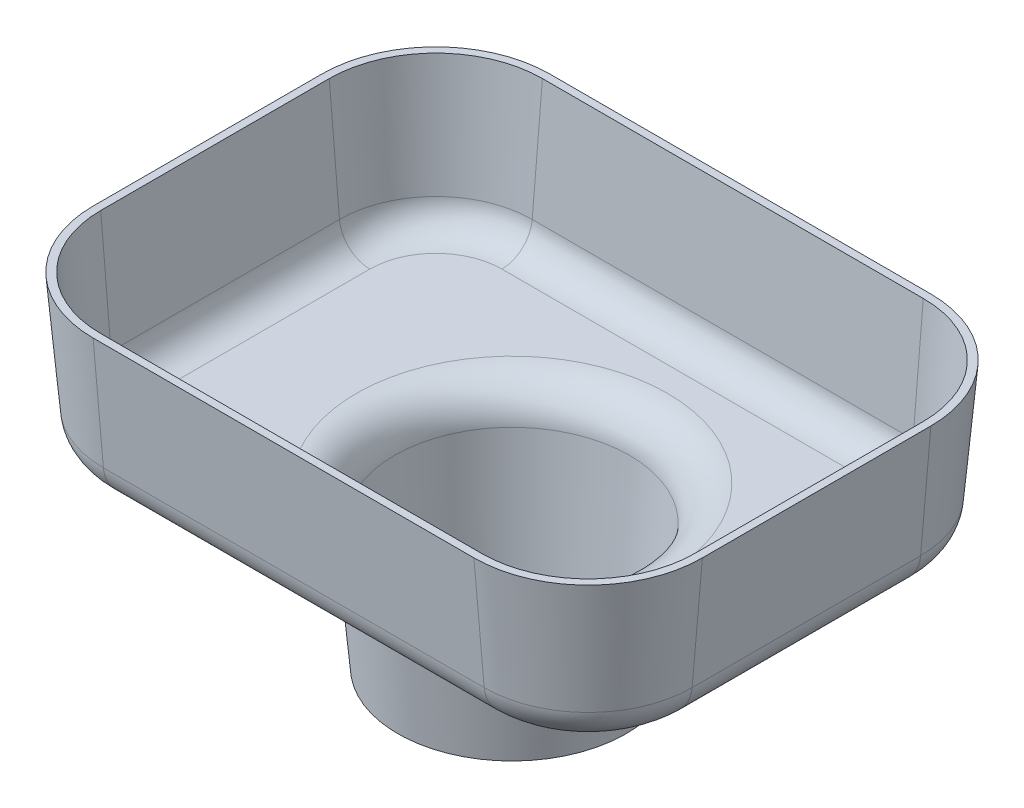
SolidWorks part; units mm, degrees
ref_plane "Front Plane" through (0, 0, 0) normal (0, 0, 1) x (1, 0, 0)
ref_plane "Top Plane" through (0, 0, 0) normal (0, 1, 0) x (1, 0, 0)
ref_plane "Right Plane" through (0, 0, 0) normal (1, 0, 0) x (0, 0, -1)
sketch "Sketch1" plane through (0, 0, 0) normal (0, 1, 0) x (1, 0, 0)
  line L1 (31.75, -38.1) -> (-31.75, -38.1)
  line L2 (50.8, -19.05) -> (50.8, 19.05)
  line L3 (31.75, 38.1) -> (-31.75, 38.1)
  line L4 (-50.8, -19.05) -> (-50.8, 19.05)
  line L5 (50.8, -38.1) -> (-50.8, 38.1) construction
  line L6 (50.8, 38.1) -> (-50.8, -38.1) construction
  arc A0 (-50.8, 19.05) -> (-31.75, 38.1) centre (-31.75, 19.05) cw
  arc A1 (-50.8, -19.05) -> (-31.75, -38.1) centre (-31.75, -19.05) ccw
  arc A2 (50.8, 19.05) -> (31.75, 38.1) centre (31.75, 19.05) ccw
  arc A3 (31.75, -38.1) -> (50.8, -19.05) centre (31.75, -19.05) ccw
  point P0 (0, 0)
  dimension "D3" = 19.05
  dimension "D4" = 19.05
  dimension "D5" = 19.05
  dimension "D6" = 19.05
  dimension "D1" = 76.2
  dimension "D2" = 101.6
extrude "Boss-Extrude1" add sketch "Sketch1" against normal blind 25.4 draft 5
ref_plane "Plane1" through (0, -50.8, 0) normal (0, -1, 0) x (-1, 0, 0)
sketch "Sketch3" plane through (0, -50.8, 0) normal (0, -1, 0) x (-1, 0, 0)
  circle A0 centre (0, 0) radius 19.05
  dimension "D1" = 38.1
extrude "Boss-Extrude2" add sketch "Sketch3" against normal up to next draft 5 draft outward yes
fillet "Fillet1" radius 5.08 1 edges at (0, -25.4, -21.2722)
fillet "Fillet2" radius 6.35 8 edges at (48.5778, -25.4, 0) (43.649, -25.4, 30.949) (0, -25.4, 35.8778) (-43.649, -25.4, 30.949) (-48.5778, -25.4, 0) (-43.649, -25.4, -30.949) (0, -25.4, -35.8778) (43.649, -25.4, -30.949)
shell "Shell1" thickness 1.27
